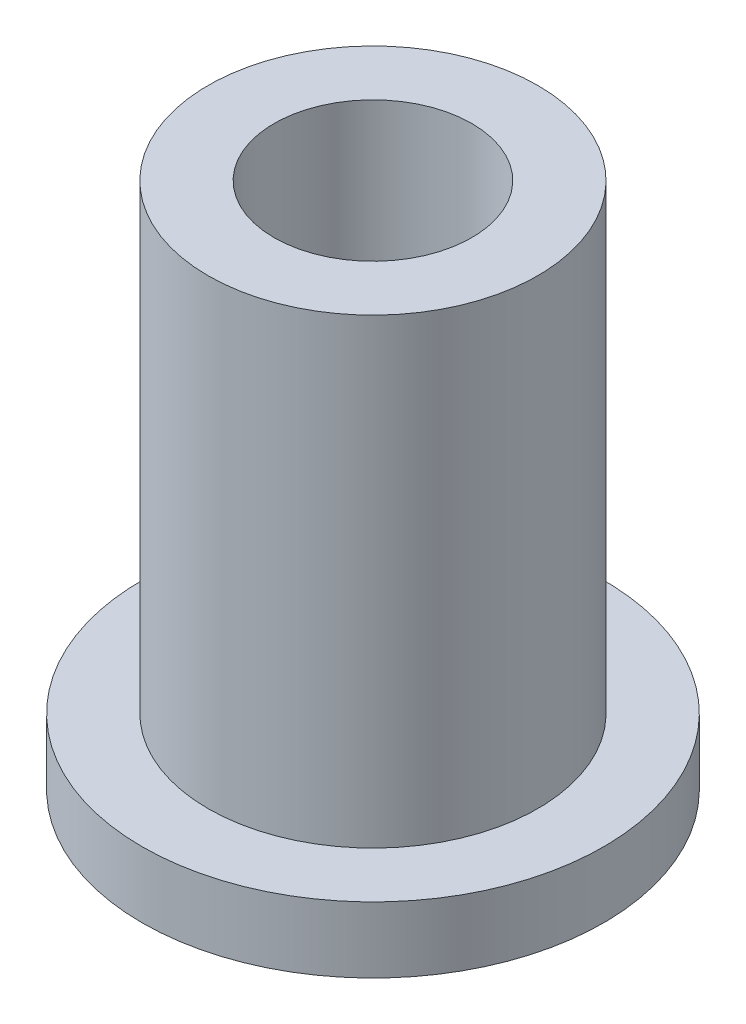
SolidWorks part; units mm, degrees
ref_plane "Front" through (0, 0, 0) normal (0, 0, 1) x (1, 0, 0)
ref_plane "Top" through (0, 0, 0) normal (0, 1, 0) x (1, 0, 0)
ref_plane "Right" through (0, 0, 0) normal (1, 0, 0) x (0, 0, -1)
sketch "Sketch1" plane through (0, 0, 0) normal (0, 1, 0) x (1, 0, 0)
  circle A0 centre (0, 0) radius 5.5562
  circle A1 centre (0, 0) radius 2.3812
  dimension "D1" = 11.1125
  dimension "D2" = 4.7625
extrude "Boss-Extrude1" add sketch "Sketch1" along normal blind 1.5875
sketch "Sketch2" plane through (0, 1.5875, 0) normal (0, 1, 0) x (1, 0, 0)
  circle A0 centre (0, 0) radius 3.9688
  circle A1 centre (0, 0) radius 2.3812
  circle A2 centre (0, 0) radius 2.3812 construction
  dimension "D1" = 7.9375
extrude "Boss-Extrude2" add sketch "Sketch2" along normal blind 11.1125
